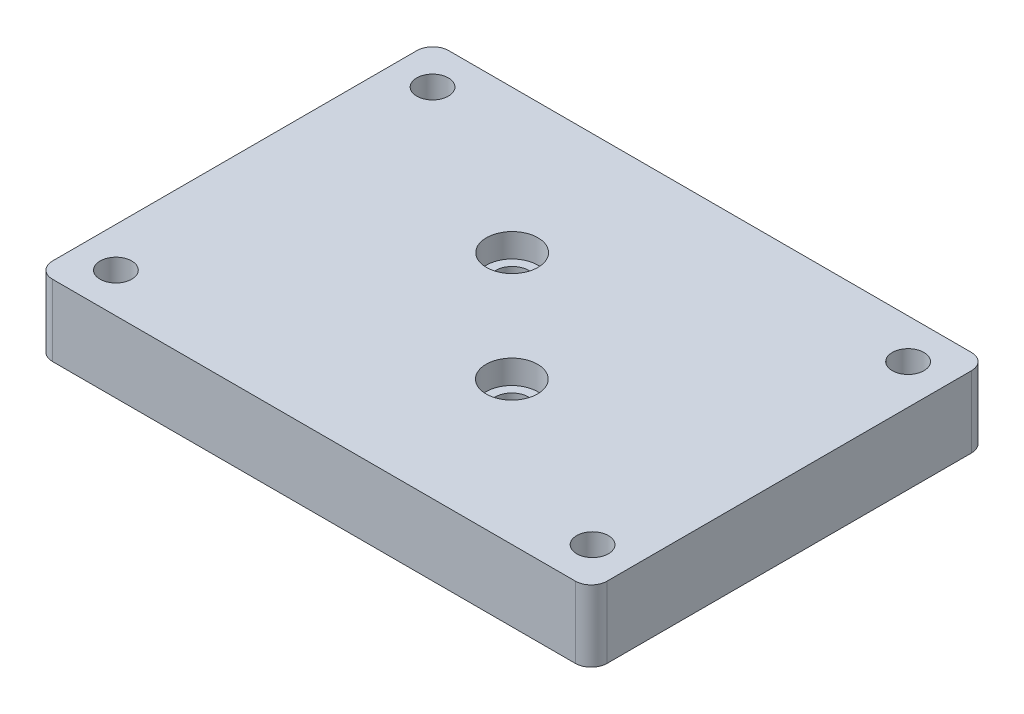
SolidWorks part; units mm, degrees
ref_plane "Front Plane" through (0, 0, 0) normal (0, 0, 1) x (1, 0, 0)
ref_plane "Top Plane" through (0, 0, 0) normal (0, 1, 0) x (1, 0, 0)
ref_plane "Right Plane" through (0, 0, 0) normal (1, 0, 0) x (0, 0, -1)
sketch "Sketch1" plane through (0, 0, 0) normal (0, 1, 0) x (1, 0, 0)
  line L0 (-66.7472, 20.103) -> (9.1561, 20.103) construction
  line L5 (11.5199, -19.897) -> (-67.7187, -19.897) construction
  line L7 (6.4992, 25.103) -> (-63.5008, 25.103)
  line L8 (6.4992, 25.103) -> (6.4992, -24.897)
  line L9 (6.4992, -24.897) -> (-63.5008, -24.897)
  line L10 (-63.5008, 25.103) -> (-63.5008, -24.897)
  line L11 (6.4992, 25.103) -> (-63.5008, -24.897) construction
  line L12 (6.4992, -24.897) -> (-63.5008, 25.103) construction
  line L14 (1.4992, 32.1738) -> (1.4992, -50.7992) construction
  line L15 (1.4992, -50.7992) -> (-58.5008, -50.7992) construction
  line L16 (-58.5008, -50.7992) -> (-58.5008, 32.1738) construction
  circle A1 centre (-58.5288, 20.103) radius 2
  circle A2 centre (-58.5008, -19.897) radius 2
  circle A4 centre (1.6001, -19.8302) radius 2
  circle A9 centre (1.4992, 20.103) radius 2
  circle A10 centre (-28.5008, 0.103) radius 6.5
  point P0 (0, 0)
  point P8 (-28.5008, 0.103)
  dimension "D1" = 5
  dimension "D4" = 5
  dimension "D5" = 50
  dimension "D3" = 5
  dimension "D2" = 5
  dimension "D6" = 70
extrude "Boss-Extrude1" add sketch "Sketch1" along normal blind 9
sketch "Sketch3" plane through (0, 9, 0) normal (0, 1, 0) x (1, 0, 0)
  circle A0 centre (-58.5288, 20.103) radius 2.5
  circle A1 centre (1.4992, 20.103) radius 2.5
  circle A2 centre (1.6001, -19.8302) radius 2.5
  circle A3 centre (-58.5008, -19.897) radius 2.5
sketch "Sketch5" plane through (0, 9, 0) normal (0, 1, 0) x (1, 0, 0)
  line L5 (-38.2608, -9.677) -> (-18.7208, 9.903) construction
  line L6 (-35.4063, 7.0285) -> (-21.5953, -6.8225) construction
  circle A1 centre (-35.4063, 7.0285) radius 2.1
  circle A2 centre (-21.5953, -6.8225) radius 2.1
  point P0 (-28.5008, 0.103)
  dimension "D1" = 9.78
  dimension "D2" = 9.78
extrude "Cut-Extrude1" cut sketch "Sketch5" against normal blind 9
sketch "Sketch6" plane through (0, 9, 0) normal (0, 1, 0) x (1, 0, 0)
  circle A0 centre (-35.4063, 7.0285) radius 3.25
  circle A1 centre (-21.5953, -6.8225) radius 3.25
extrude "Cut-Extrude2" cut sketch "Sketch6" against normal blind 3
fillet "Fillet1" radius 2 4 edges at (6.4992, 4.5, 24.897) (6.4992, 4.5, -25.103) (-63.5008, 4.5, -25.103) (-63.5008, 4.5, 24.897)
sketch "Sketch7" plane through (0, 0, 0) normal (0, -1, 0) x (1, 0, 0)
  circle A1 centre (-28.5008, -0.103) radius 6.5
sketch "Sketch8" plane through (0, 9, 0) normal (0, 1, 0) x (1, 0, 0)
  circle A0 centre (-28.5008, 0.103) radius 6.5
extrude "Boss-Extrude3" add sketch "Sketch8" against normal blind 4.5
